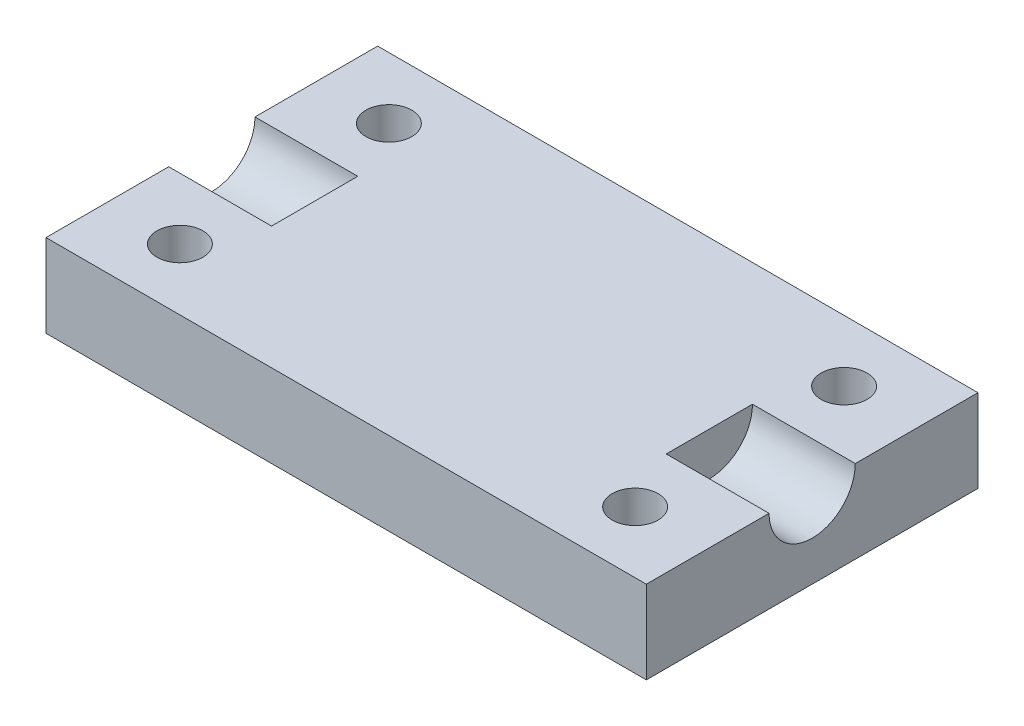
SolidWorks part; units mm, degrees
ref_plane "Front Plane" through (0, 0, 0) normal (0, 0, 1) x (1, 0, 0)
ref_plane "Top Plane" through (0, 0, 0) normal (0, 1, 0) x (1, 0, 0)
ref_plane "Right Plane" through (0, 0, 0) normal (1, 0, 0) x (0, 0, -1)
sketch "Sketch1" plane through (0, 0, 0) normal (0, 1, 0) x (1, 0, 0)
  line L1 (-22.987, -12.7) -> (22.987, -12.7)
  line L2 (-22.987, -12.7) -> (-22.987, 12.7)
  line L3 (-22.987, 12.7) -> (22.987, 12.7)
  line L4 (22.987, -12.7) -> (22.987, 12.7)
  line L5 (-22.987, -12.7) -> (22.987, 12.7) construction
  line L6 (-22.987, 12.7) -> (22.987, -12.7) construction
  point P0 (0, 0)
  dimension "D1" = 45.974
  dimension "D2" = 25.4
extrude "Boss-Extrude1" add sketch "Sketch1" against normal blind 6.35
sketch "Sketch2" plane through (22.987, 0, 0) normal (1, 0, 0) x (0, 0, -1)
  line L0 (-12.7, 0) -> (12.7, 0) construction
  circle A0 centre (0, 0) radius 3.302
  dimension "D1" = 6.604
extrude "Cut-Extrude1" cut sketch "Sketch2" against normal blind 7.874
sketch "Sketch3" plane through (-22.987, 0, 0) normal (-1, 0, 0) x (0, 0, 1)
  circle A0 centre (0, 0) radius 3.302
  dimension "D1" = 6.604
extrude "Cut-Extrude2" cut sketch "Sketch3" against normal blind 7.874
sketch "Sketch4" plane through (0, 0, 0) normal (0, 1, 0) x (1, 0, 0)
  line L0 (-22.987, -3.302) -> (-22.987, -12.7) construction
  line L1 (-22.987, 12.7) -> (-22.987, 3.302) construction
  line L2 (22.987, 3.302) -> (22.987, 12.7) construction
  line L3 (22.987, -12.7) -> (22.987, -3.302) construction
  line L4 (-22.987, 8.001) -> (22.987, 8.001) construction
  line L5 (-22.987, -8.001) -> (22.987, -8.001) construction
  line L7 (17.4308, -8.001) -> (-17.4308, -8.001) construction
  line L8 (17.4308, -8.001) -> (17.4308, 8.001) construction
  line L9 (17.4308, 8.001) -> (-17.4308, 8.001) construction
  line L10 (-17.4308, -8.001) -> (-17.4308, 8.001) construction
  line L11 (17.4308, -8.001) -> (-17.4308, 8.001) construction
  line L12 (17.4308, 8.001) -> (-17.4308, -8.001) construction
  circle A0 centre (17.4308, -8.001) radius 1.7589
  circle A1 centre (17.4308, 8.001) radius 1.7589
  circle A2 centre (-17.4308, 8.001) radius 1.7589
  circle A3 centre (-17.4308, -8.001) radius 1.7589
  point P20 (0, 0)
  dimension "D1" = 16.002
  dimension "D2" = 34.8615
  dimension "D3" = 3.5179
extrude "Cut-Extrude11" cut sketch "Sketch4" against normal up to next
